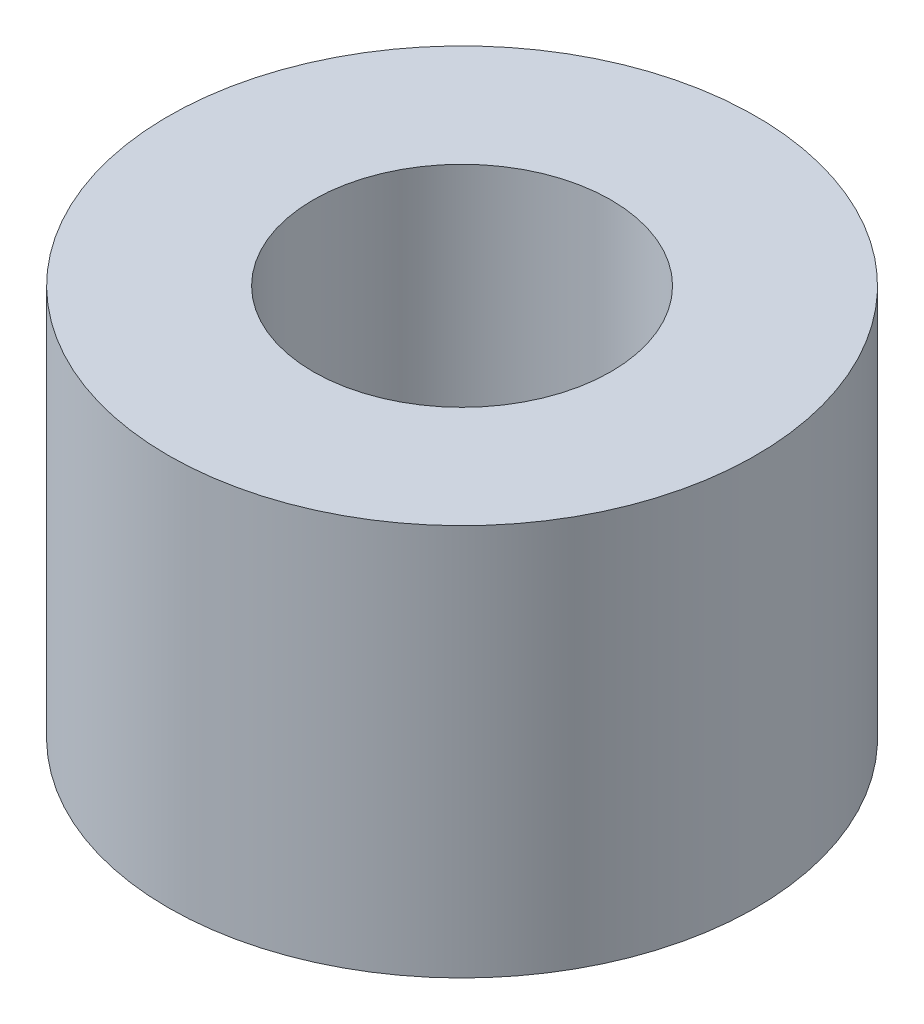
SolidWorks part; units mm, degrees
material "Delrin 2700 NC010, Low Viscosity Acetal Copolymer (SS)"
ref_plane "Front Plane" through (0, 0, 0) normal (0, 0, 1) x (1, 0, 0)
ref_plane "Top Plane" through (0, 0, 0) normal (0, 1, 0) x (1, 0, 0)
ref_plane "Right Plane" through (0, 0, 0) normal (1, 0, 0) x (0, 0, -1)
sketch "Sketch1" plane through (0, 0, 0) normal (0, 1, 0) x (1, 0, 0)
  circle A0 centre (0, 0) radius 4.7625
  circle A1 centre (0, 0) radius 2.413
  dimension "D1" = 9.525
  dimension "D2" = 4.826
extrude "Boss-Extrude1" add sketch "Sketch1" along normal blind 6.35
